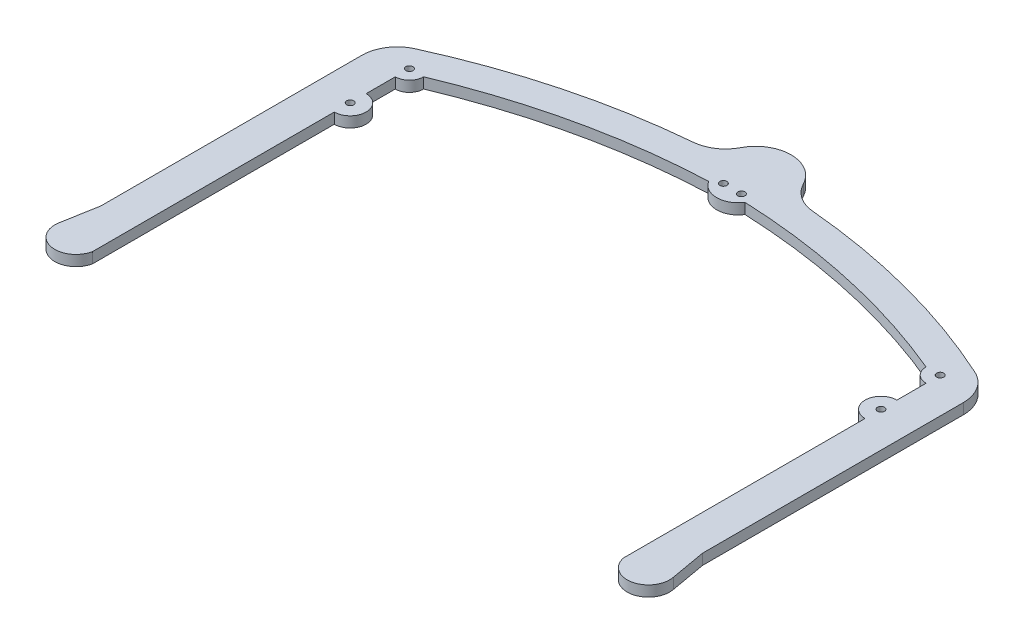
SolidWorks part; units mm, degrees
ref_plane "Front Plane" through (0, 0, 0) normal (0, 0, 1) x (1, 0, 0)
ref_plane "Top Plane" through (0, 0, 0) normal (0, 1, 0) x (1, 0, 0)
ref_plane "Right Plane" through (0, 0, 0) normal (1, 0, 0) x (0, 0, -1)
sketch "Sketch2" plane through (0, 0, 0) normal (0, 1, 0) x (1, 0, 0)
  line L0 (0, 0) -> (0, 117.1859) construction
  line L1 (85, 97.1859) -> (75, 92.6033) construction
  line L2 (85, 97.1859) -> (85, 17.1859)
  line L3 (75, 92.6033) -> (75, 4.8141)
  line L4 (0, 117.1859) -> (0, 127.1859) construction
  line L5 (0, 117.1859) -> (0, 109.1859)
  line L6 (0, 117.1859) -> (85, 117.1859) construction
  line L7 (85, 17.1859) -> (86.7633, 7.1859)
  line L8 (0, 127.1859) -> (0, 117.1859)
  line L9 (0, 0) -> (102.9156, 0) construction
  line L10 (75, 4.8141) -> (86.7633, 7.1859) construction
  arc A0 (0, 117.1859) -> (85, 97.1859) centre (0, -73.4391) cw
  arc A1 (0, 109.1859) -> (75, 92.6033) centre (-2.8096, -81.4184) cw
  arc A2 (0, 127.1859) -> (9.9966, 116.9236) centre (0, 117.1859) cw
  arc A3 (75, 4.8141) -> (86.7633, 7.1859) centre (80.8816, 6) ccw
  dimension "D5" = 10
  dimension "D9" = 6
  dimension "D1" = 10
  dimension "D2" = 8
  dimension "D3" = 20
  dimension "D4" = 85
  dimension "D6" = 10
  dimension "D7" = 11
  dimension "D8" = 170
  dimension "D10" = 100
extrude "Boss-Extrude2" add sketch "Sketch2" along normal blind 3 contours A2 L8 A0 | L3 A3 L7 L2 A0 L5 A1
fillet "Fillet3" radius 10 2 edges at (9.9966, 1.5, -116.9236) (85, 1.5, -97.1859)
mirror "Mirror3" about plane through (0, 3, 0) normal (1, 0, 0) of "Fillet3", "Boss-Extrude2"
sketch "Sketch4" plane through (0, 3, 0) normal (0, 1, 0) x (1, 0, 0)
  line L0 (75, 92.6033) -> (75, 4.8141) construction
  line L1 (0, 106.1859) -> (0, 109.1859)
  arc A0 (71, 94.3372) -> (75, 90.3372) centre (75, 94.3372) ccw
  arc A1 (75, 92.6033) -> (0, 109.1859) centre (-2.8096, -81.4184) ccw construction
  arc A2 (75, 82.1033) -> (75, 73.1033) centre (75, 77.6033) ccw
  arc A3 (5.1104, 109.042) -> (0, 106.1859) centre (0, 112.1859) cw
  arc M8 (0, 109.1859) -> (75, 92.6033) centre (-2.8096, -81.4184) cw
  line M9 (75, 92.6033) -> (75, 4.8141)
  dimension "D1" = 4
  dimension "D2" = 4.5
  dimension "D3" = 6
  dimension "D4" = 3
  dimension "D5" = 15
extrude "Boss-Extrude3" add sketch "Sketch4" against normal blind 3 contours A3 L1 M8 | A0 M8 M9 | A2 M9
mirror "Mirror4" about plane through (0, 0, 0) normal (1, 0, 0) of "Boss-Extrude3"
hole_wizard "Ø2.0 (2) Diameter Hole1" positions "3DSketch1" profile "Sketch5" hole size "Ø2.0" standard "ISO" end condition through all
sketch3d "3DSketch1"
  line L0 (75, 0, -77.6033) -> (75, 3, -77.6033) construction
  line L1 (75, 3, -90.3372) -> (75, 3, -94.3372) construction
  line L3 (71, 3, -94.3372) -> (75, 3, -94.3372) construction
  line L5 (75, 3, -82.1033) -> (75, 3, -73.1033) construction
  line L6 (75, 3, -73.1033) -> (75, 3, -4.8141) construction
  arc A2 (5.1104, 3, -109.042) -> (-5.1104, 3, -109.042) centre (0, 3, -112.1859) ccw construction
  arc A3 (75, 3, -82.1033) -> (75, 3, -73.1033) centre (75, 3, -77.6033) ccw construction
  point P0 (2.5552, 3, -110.614)
  point P2 (75, 3, -94.3372)
  point P4 (75, 3, -77.6033)
  point P21 (0, -3, -112.1859)
  point P39 (75, 7.5, -77.6033)
  dimension "D2" = 3
  dimension "D1" = 3
sketch "Sketch5" plane through (2.5552, 3, -110.614) normal (1, 0, 0) x (0, 0, 1)
  line L0 (0, 0) -> (0, 3)
  line L1 (0, 3) -> (1, 3)
  line L2 (1, 3) -> (1, 0)
  line L5 (1, 0) -> (0, 0)
  line L11 (0, -6.35) -> (0, 107.95) construction
  dimension "Thru Hole Dia." = 2
  dimension "Thru Hole Depth" = 3
mirror "Mirror5" about plane through (0, 0, 0) normal (1, 0, 0) of "Ø2.0 (2) Diameter Hole1"
sketch "Sketch6" plane through (0, 3, 0) normal (0, 1, 0) x (1, 0, 0)
  line L0 (0, 127.1859) -> (0, 73.1033) construction
  line L1 (0, 73.1033) -> (75, 73.1033) construction
  line L2 (75, 73.1033) -> (75, 4.8141) construction
  line L3 (0, 113.614) -> (76.7824, 113.614) construction
  line L4 (78.5, 97.3372) -> (78.5, 72.3372)
  line L5 (0, 113.614) -> (0, 88.614)
  arc A0 (8.8758, 121.7925) -> (-8.8758, 121.7925) centre (0, 117.1859) ccw construction
  arc A1 (0, 113.614) -> (78.5, 97.3372) centre (0, -83.8207) cw
  arc A2 (0, 88.614) -> (78.5, 72.3372) centre (0, -108.8207) cw
  circle A4 centre (2.5552, 110.614) radius 1 construction
  circle A5 centre (75, 94.3372) radius 1 construction
  point P22 (2.5552, 110.614)
  point P23 (75, 94.3372)
  point P25 (75, 77.6033)
  dimension "D2" = 3
  dimension "D4" = 3.5
  dimension "D1" = 25
  dimension "D3" = 3
